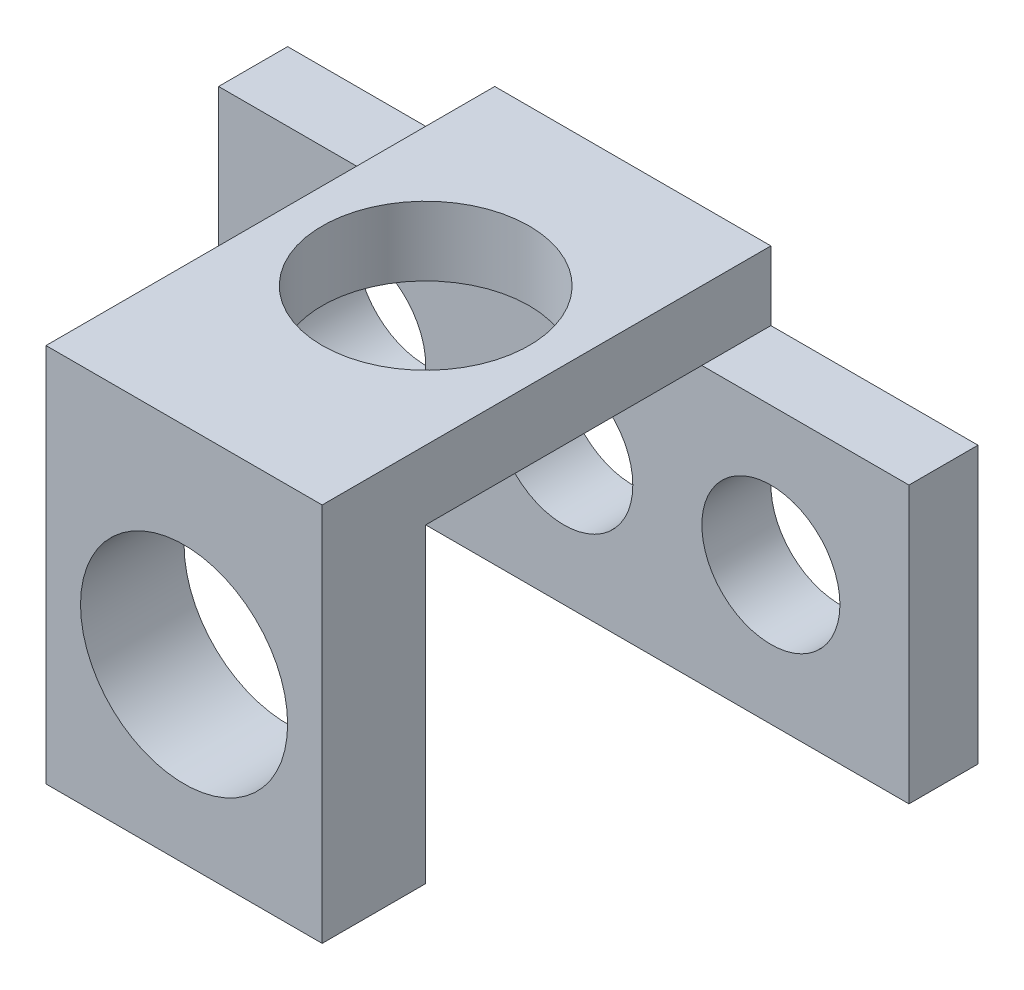
SolidWorks part; units mm, degrees
ref_plane "Plano frontal" through (0, 0, 0) normal (0, 0, 1) x (1, 0, 0)
ref_plane "Plano superior" through (0, 0, 0) normal (0, 1, 0) x (1, 0, 0)
ref_plane "Plano direito" through (0, 0, 0) normal (1, 0, 0) x (0, 0, -1)
sketch "Esboço1" plane through (0, 0, 0) normal (0, 1, 0) x (1, 0, 0)
  line L0 (-50, 0) -> (50, 0)
  line L1 (50, 0) -> (50, 10)
  line L2 (50, 10) -> (-50, 10)
  line L3 (-50, 10) -> (-50, 0)
  dimension "D1" = 10
  dimension "D2" = 100
extrude "Ressalto-extrusão1" add sketch "Esboço1" along normal blind 40
sketch "Esboço3" plane through (0, 0, -10) normal (0, 0, -1) x (-1, 0, 0)
  line L0 (-20, 40) -> (-20, 50)
  line L1 (-50, 40) -> (50, 40) construction
  line L2 (-20, 50) -> (20, 50)
  line L3 (20, 50) -> (20, 40)
  line L4 (20, 40) -> (-20, 40)
  line L5 (-50, 40) -> (-50, 0) construction
  dimension "D1" = 40
  dimension "D2" = 30
  dimension "D3" = 10
extrude "Ressalto-extrusão2" add sketch "Esboço3" against normal blind 65 contours L2 L3 L4 L0
sketch "Esboço4" plane through (0, 40, 0) normal (0, -1, 0) x (1, 0, 0)
  line L0 (-20, 40) -> (20, 40)
  line L1 (-20, 55) -> (-20, 0) construction
  line L2 (20, 55) -> (20, 0) construction
  line L3 (-20, 40) -> (-20, 55)
  line L4 (-20, 55) -> (20, 55)
  line L5 (20, 55) -> (20, 40)
  dimension "D1" = 40
  dimension "D2" = 15
extrude "Ressalto-extrusão3" add sketch "Esboço4" along normal blind 45
sketch "Esboço5" plane through (0, 0, 0) normal (0, 0, 1) x (1, 0, 0)
  line L0 (-50, 20) -> (50, 20) construction
  line L1 (-50, 40) -> (-50, 0) construction
  line L2 (50, 40) -> (50, 0) construction
  line L4 (20, 50) -> (-20, 50) construction
  circle A0 centre (-30, 20) radius 10
  circle A1 centre (30, 20) radius 10
  circle A2 centre (0, 20) radius 10
  point P15 (0, 50)
  dimension "D1" = 30
  dimension "D3" = 20
  dimension "D4" = 20
  dimension "D5" = 20
  dimension "D2" = 30
extrude "Corte-extrusão1" cut sketch "Esboço5" against normal through all
sketch "Esboço6" plane through (0, 0, 55) normal (0, 0, 1) x (1, 0, 0)
  line L0 (-20, 20) -> (20, 20) construction
  line L1 (-20, 50) -> (-20, -5) construction
  line L2 (20, -5) -> (20, 50) construction
  line L3 (-50, 40) -> (-20, 40) construction
  circle A0 centre (30, 20) radius 10 construction
  circle A2 centre (0, 20) radius 15
  dimension "D2" = 30
  dimension "D1" = 20
sketch "Esboço7" plane through (0, 50, 0) normal (0, 1, 0) x (1, 0, 0)
  line L2 (-20, -55) -> (20, -55) construction
  line L3 (-20, 0) -> (20, 0) construction
  line L4 (-20, -55) -> (-20, 10) construction
  line L5 (20, -55) -> (20, 10) construction
  circle A0 centre (0, -20) radius 15
  point P18 (0, 0)
  dimension "D3" = 30
  dimension "D1" = 55
  dimension "D2" = 20
  dimension "D4" = 20
extrude "Corte-extrusão3" cut sketch "Esboço7" against normal blind 45
extrude "Corte-extrusão4" cut sketch "Esboço6" against normal blind 21 contours A2
